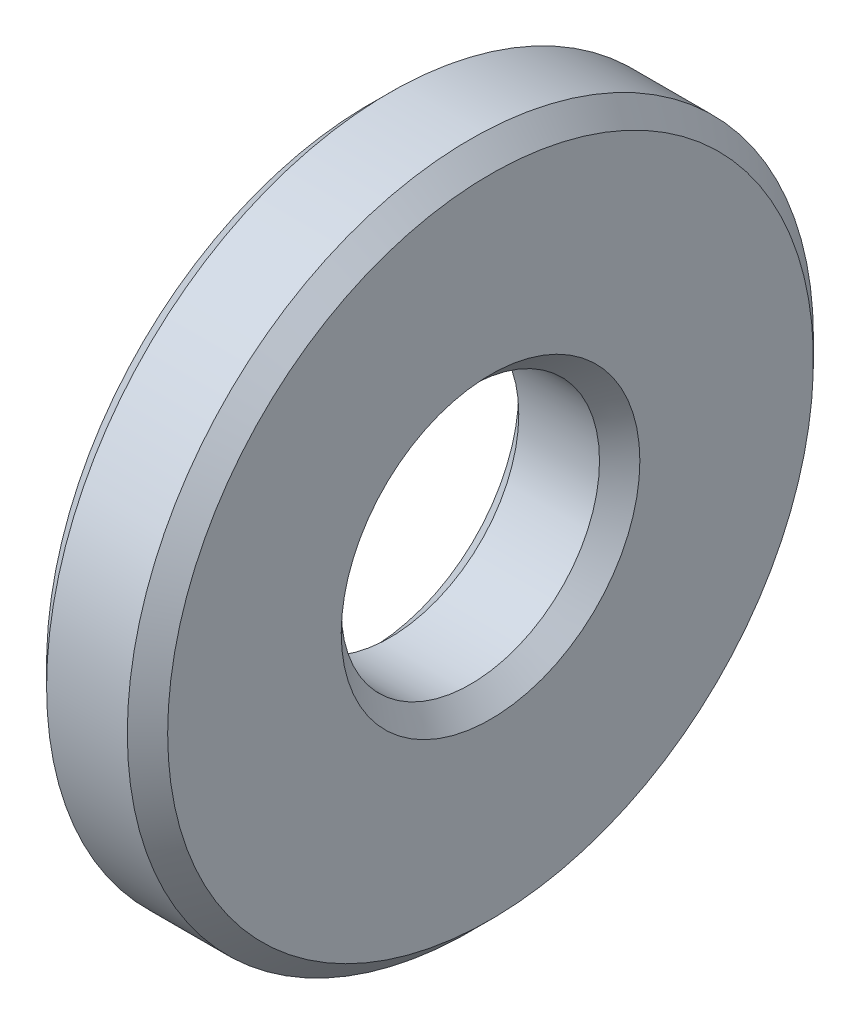
SolidWorks part; units mm, degrees
ref_plane "Plan1" through (0, 0, 0) normal (0, 0, 1) x (1, 0, 0)
ref_plane "Plan2" through (0, 0, 0) normal (0, 1, 0) x (1, 0, 0)
ref_plane "Plan3" through (0, 0, 0) normal (1, 0, 0) x (0, 0, -1)
sketch "Esquisse1" plane through (0, 0, 0) normal (0, 0, 1) x (1, 0, 0)
  line L0 (0, 0) -> (20, 0) construction
  line L2 (0, 3.2) -> (3, 3.2)
  line L3 (0, 3.2) -> (0, 8.5)
  line L4 (0, 8.5) -> (3, 8.5)
  line L5 (3, 3.2) -> (3, 8.5)
  dimension "D1" = 3
  dimension "D2" = 3.2
  dimension "D3" = 8.5
revolve "Base-Révolution" add sketch "Esquisse1" angle 360 about L0
chamfer "Chanfrein1" distance 0.5 angle 45 4 edges at (0, 0, 3.2) (3, 0, 3.2) (3, 0, 8.5) (0, 0, 8.5)
